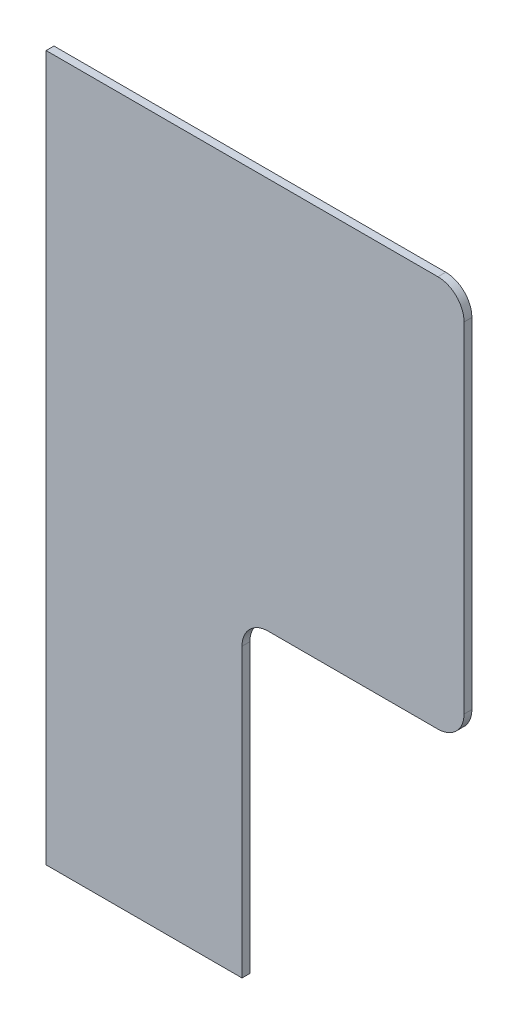
SolidWorks part; units mm, degrees
ref_plane "Front" through (0, 0, 0) normal (0, 0, 1) x (1, 0, 0)
ref_plane "Top" through (0, 0, 0) normal (0, 1, 0) x (1, 0, 0)
ref_plane "Right" through (0, 0, 0) normal (1, 0, 0) x (0, 0, -1)
sketch "Sketch1" plane through (0, 0, 0) normal (0, 0, 1) x (1, 0, 0)
  line L25 (0, 0) -> (0, -120) construction
  line L28 (85, 0) -> (-75, 0) construction
  line L30 (85, 150) -> (-75, -120) construction
  line L31 (85, -120) -> (-75, 150) construction
  line L32 (-75, -120) -> (-75, 150) construction
  line L33 (85, 150) -> (-75, 150) construction
  line L34 (85, -120) -> (85, 150) construction
  line L35 (85, -120) -> (-75, -120) construction
  line L37 (-75, -120) -> (-75, 150)
  line L38 (0, -120) -> (-75, -120)
  line L39 (0, -10) -> (0, -120)
  line L40 (75, 0) -> (10, 0)
  line L41 (85, 140) -> (85, 10)
  line L42 (-75, 150) -> (75, 150)
  arc A8 (75, 150) -> (85, 140) centre (75, 140) cw
  arc A9 (85, 10) -> (75, 0) centre (75, 10) cw
  arc A10 (10, 0) -> (0, -10) centre (10, -10) ccw
  dimension "D2" = 10
  dimension "D1" = 160
  dimension "D3" = 85
  dimension "D4" = 150
  dimension "D5" = 120
extrude "Boss-Extrude1" add sketch "Sketch1" along normal blind 3
